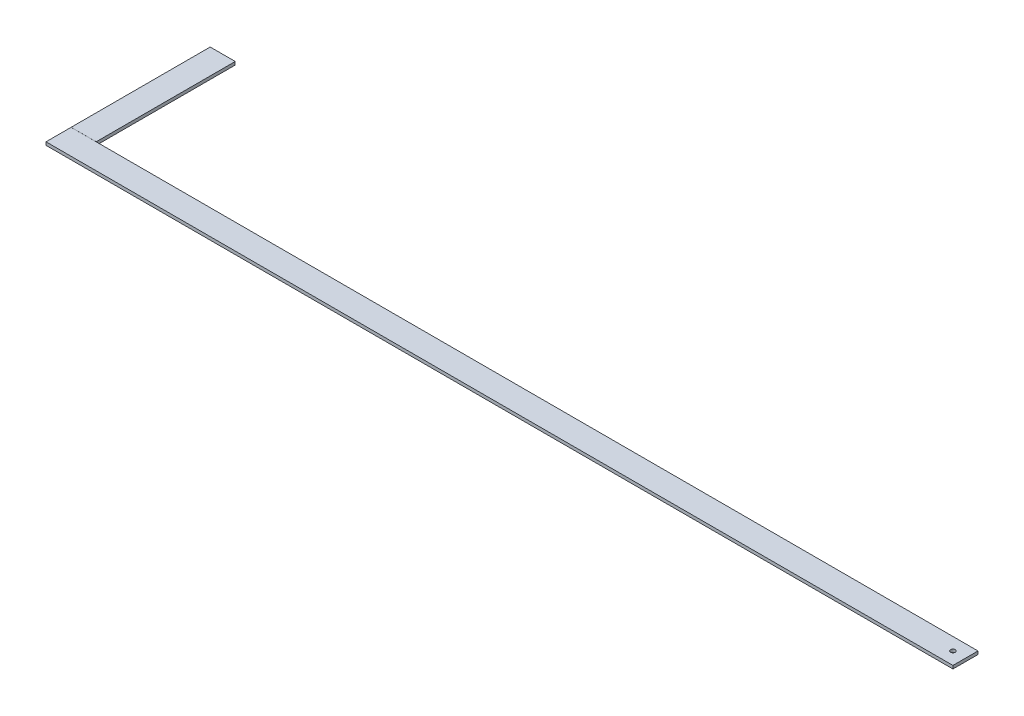
SolidWorks part; units mm, degrees
ref_plane "Alzado" through (0, 0, 0) normal (0, 0, 1) x (1, 0, 0)
ref_plane "Planta" through (0, 0, 0) normal (0, 1, 0) x (1, 0, 0)
ref_plane "Vista lateral" through (0, 0, 0) normal (1, 0, 0) x (0, 0, -1)
sketch "Croquis2" plane through (0, 0, 0) normal (0, 0, 1) x (1, 0, 0)
  line L1 (-25.4, 67.5) -> (25.4, 67.5)
  line L2 (-25.4, 67.5) -> (-25.4, -67.5)
  line L3 (-25.4, -67.5) -> (25.4, -67.5)
  line L4 (25.4, 67.5) -> (25.4, -67.5)
  line L5 (-25.4, 67.5) -> (25.4, -67.5) construction
  line L6 (-25.4, -67.5) -> (25.4, 67.5) construction
  point P0 (0, 0)
  dimension "D1" = 135
  dimension "D2" = 50.8
extrude "Saliente-Extruir1" add sketch "Croquis2" along normal blind 6.31
sketch "Croquis3" plane through (0, 0, 6.31) normal (0, 0, 1) x (1, 0, 0)
  line L1 (-25.4, -61.19) -> (25.4, -61.19)
  line L2 (-25.4, -61.19) -> (-25.4, -67.5)
  line L3 (-25.4, -67.5) -> (25.4, -67.5)
  line L4 (25.4, -61.19) -> (25.4, -67.5)
  line L5 (-25.4, -61.19) -> (25.4, -67.5) construction
  line L6 (-25.4, -67.5) -> (25.4, -61.19) construction
  point P0 (0, -64.345)
  dimension "D1" = 6.31
  dimension "D2" = 50.8
extrude "Saliente-Extruir2" add sketch "Croquis3" along normal blind 513.44
sketch "Croquis4" plane through (25.4, 0, 0) normal (1, 0, 0) x (0, 0, -1)
  line L1 (-468.95, -67.5) -> (-519.75, -67.5)
  line L2 (-468.95, -67.5) -> (-468.95, -61.19)
  line L3 (-468.95, -61.19) -> (-519.75, -61.19)
  line L4 (-519.75, -67.5) -> (-519.75, -61.19)
  line L5 (-468.95, -67.5) -> (-519.75, -61.19) construction
  line L6 (-468.95, -61.19) -> (-519.75, -67.5) construction
  point P0 (-494.35, -64.345)
  dimension "D1" = 50.8
extrude "Saliente-Extruir3" add sketch "Croquis4" along normal blind 1787.3
sketch "Croquis9" plane through (0, 0, 519.75) normal (0, 0, 1) x (1, 0, 0)
  line L0 (1812.7, -61.19) -> (-25.4, -61.19) construction
  line L1 (1761.9, -61.19) -> (1812.7, -61.19)
  line L2 (1761.9, -61.19) -> (1761.9, -67.5)
  line L3 (1761.9, -67.5) -> (1812.7, -67.5)
  line L4 (1812.7, -61.19) -> (1812.7, -67.5)
  line L5 (1761.9, -61.19) -> (1812.7, -67.5) construction
  line L6 (1761.9, -67.5) -> (1812.7, -61.19) construction
  point P0 (1787.3, -64.345)
  dimension "D1" = 50.8
sketch3d "Croquis3D3"
  line L0 (1787.3, -64.345, 519.75) -> (1787.3, -64.345, 642.06)
  line L1 (1787.3, -64.345, 642.06) -> (1787.3, 66.675, 642.06)
  line L2 (1787.3, 66.675, 642.06) -> (1787.3, 66.675, 1436.06)
  dimension "D1" = 122.31
  dimension "D2" = 131.02
  dimension "D3" = 794
sweep "Barrer2" add profiles "Croquis9" path "Croquis3D3"
sketch "Croquis11" plane through (-25.4, 0, 0) normal (-1, 0, 0) x (0, 0, 1)
  line L0 (0, 67.5) -> (-31.6013, 124.8087)
  line L1 (-31.6013, 124.8087) -> (-26.0757, 127.8557)
  line L2 (-26.0757, 127.8557) -> (6.31, 67.5)
  line L3 (0, 67.5) -> (6.31, 67.5)
  line L4 (0, 67.5) -> (0, -67.5) construction
  dimension "D1" = 6.31
  dimension "D2" = 151.127
  dimension "D3" = 65.4441
extrude "Saliente-Extruir4" add sketch "Croquis11" against normal blind 98
sketch "Croquis12" plane through (0, 69.83, 0) normal (0, 1, 0) x (1, 0, 0)
  line L0 (1787.3, -1436.06) -> (1787.3, -1403.06) construction
  line L1 (1787.3, -642.06) -> (1787.3, -1436.06) construction
  line L2 (1787.3, -1403.06) -> (1787.3, -1183.06) construction
  circle A0 centre (1787.3, -1403.06) radius 5
  circle A1 centre (1787.3, -1183.06) radius 5
  dimension "D3" = 10
  dimension "D4" = 10
  dimension "D1" = 33
  dimension "D2" = 220
extrude "Cortar-Extruir1" cut sketch "Croquis12" against normal blind 10
sketch "Croquis13" plane through (1812.7, 0, 0) normal (1, 0, 0) x (0, 0, -1)
  line L0 (-645.215, 56.7163) -> (-638.905, 56.7163)
  line L1 (-645.215, -67.5) -> (-645.215, 63.52) construction
  line L2 (-638.905, -61.19) -> (-638.905, 69.83) construction
  line L3 (-638.905, 56.7163) -> (-638.905, 69.83)
  line L4 (-638.905, 69.83) -> (-1436.06, 69.83)
  line L5 (-1436.06, 69.83) -> (-1436.06, 63.52)
  line L6 (-1436.06, 63.52) -> (-645.215, 63.52)
  line L7 (-645.215, 63.52) -> (-645.215, 56.7163)
  dimension "D1" = 13.1137
extrude "Cortar-Extruir2" cut sketch "Croquis13" against normal blind 73
sketch "Croquis16" plane through (0, 17.7188, 33.0216) normal (0, 0.4728, 0.8812) x (1, 0, 0)
  line L0 (25.4, 56.495) -> (25.4, 124.9905)
  line L1 (72.6, 124.9905) -> (-25.4, 124.9905) construction
  line L2 (25.4, 124.9905) -> (72.6, 124.9905)
  line L3 (72.6, 124.9905) -> (72.6, 56.495)
  line L4 (72.6, 56.495) -> (25.4, 56.495)
extrude "Cortar-Extruir5" cut sketch "Croquis16" against normal blind 10
sketch "Croquis17" plane through (0, -61.19, 0) normal (0, 1, 0) x (1, 0, 0)
  line L0 (25.4, -468.95) -> (-25.4, -468.95)
  line L1 (-25.4, -519.75) -> (-25.4, -6.31) construction
  line L2 (-25.4, -468.95) -> (-25.4, -468.85)
  line L3 (-25.4, -468.85) -> (25.4, -468.85)
  line L4 (25.4, -468.95) -> (25.4, -6.31) construction
  line L5 (25.4, -468.85) -> (25.4, -468.95)
  dimension "D1" = 0.1
extrude "Cortar-Extruir6" cut sketch "Croquis17" against normal blind 50.8
sketch "Croquis18" plane through (0, -61.19, 0) normal (0, 1, 0) x (1, 0, 0)
  line L0 (1761.9, -519.75) -> (1812.7, -519.75)
  line L1 (1812.7, -468.95) -> (1812.7, -638.905) construction
  line L2 (1812.7, -519.75) -> (1812.7, -519.85)
  line L3 (1812.7, -519.85) -> (1761.9, -519.85)
  line L4 (1761.9, -519.75) -> (1761.9, -638.905) construction
  line L5 (1761.9, -519.85) -> (1761.9, -519.75)
  dimension "D1" = 0.1
extrude "Cortar-Extruir7" cut sketch "Croquis18" against normal blind 50.8
sketch "Croquis19" plane through (0, -67.5, 0) normal (0, -1, 0) x (-1, 0, 0)
  line L0 (-1092.1469, -494.5495) -> (-1096.9077, -494.35) construction
  line L1 (-1096.9077, -494.35) -> (-1114.2705, -494.35) construction
  line L2 (-1135.4077, -494.35) -> (-1058.4077, -494.35) construction
  circle A0 centre (-1096.9077, -494.35) radius 4.765 construction
  circle A1 centre (-1096.9077, -494.35) radius 5
  dimension "D1" = 10
sketch "Croquis20" plane through (0, 0, 638.905) normal (0, 0, -1) x (-1, 0, 0)
  line L0 (-1787.3, 56.7163) -> (-1787.3, 22.7163) construction
  line L1 (-1761.9, 56.7163) -> (-1812.7, 56.7163) construction
  line L2 (-1787.3, -64.345) -> (-1787.3, 66.675) construction
  circle A0 centre (-1787.3, 22.7163) radius 5
  dimension "D2" = 10
  dimension "D1" = 34
extrude "Cortar-Extruir9" cut sketch "Croquis20" against normal blind 33
sketch "Croquis21" plane through (0, -67.5, 0) normal (0, -1, 0) x (-1, 0, 0)
  circle A0 centre (-900.0979, -457.445) radius 5
  circle A1 centre (-874.6979, -432.045) radius 5
sketch "Croquis24" plane through (0, -67.5, 0) normal (0, -1, 0) x (-1, 0, 0)
  circle A0 centre (-1800.0979, -507.05) radius 4.7625
  circle A1 centre (-1774.6979, -481.65) radius 4.7625
sketch "Croquis25" plane through (0, -67.5, 0) normal (0, -1, 0) x (-1, 0, 0)
  line L0 (-1782.7036, -493.1032) -> (-1787.3, -494.35) construction
  line L1 (-1787.3, -494.35) -> (-1787.3, -489.5875) construction
  circle A0 centre (-1787.3, -494.35) radius 4.7625 construction
  circle A1 centre (-1787.3, -494.35) radius 4.7625
extrude "Cortar-Extruir13" cut sketch "Croquis25" against normal blind 50
sketch "Croquis29" plane through (0, 56.7163, 0) normal (0, 1, 0) x (1, 0, 0)
  line L0 (1761.9, -645.215) -> (1761.9, -638.905)
  line L1 (1761.9, -638.905) -> (1812.7, -638.905)
  line L2 (1812.7, -638.905) -> (1812.7, -645.215)
  line L3 (1812.7, -645.215) -> (1761.9, -645.215)
extrude "Saliente-Extruir5" add sketch "Croquis29" along normal blind 100
sketch "Croquis31" plane through (1812.7, 0, 0) normal (1, 0, 0) x (0, 0, -1)
  line L0 (-519.85, -61.19) -> (-519.85, -67.5)
  line L1 (-519.85, -67.5) -> (-645.215, -67.5)
  line L2 (-645.215, -67.5) -> (-645.215, 156.7163)
  line L3 (-645.215, 156.7163) -> (-638.905, 156.7163)
  line L4 (-638.905, 156.7163) -> (-638.905, -61.19)
  line L5 (-638.905, -61.19) -> (-519.85, -61.19)
sketch "Croquis32" plane through (-25.4, 0, 0) normal (-1, 0, 0) x (0, 0, 1)
  line L0 (6.31, -61.19) -> (0, -61.19)
  line L1 (0, 67.5) -> (0, -67.5) construction
  line L2 (0, -61.19) -> (0, 67.5)
  line L3 (0, 67.5) -> (-31.6013, 124.8087)
  line L4 (-31.6013, 124.8087) -> (-26.0757, 127.8557)
  line L5 (-26.0757, 127.8557) -> (6.31, 67.5)
  line L6 (6.31, 67.5) -> (6.31, -61.19)
extrude "Cortar-Extruir17" cut sketch "Croquis32" against normal blind 68
sketch "Croquis33" plane through (0, -61.19, 0) normal (0, 1, 0) x (1, 0, 0)
  line L0 (-25.4, 0) -> (-25.4, -187)
  line L1 (-25.4, -468.85) -> (-25.4, 0) construction
  line L2 (-25.4, -187) -> (25.4, -187)
  line L3 (25.4, -468.85) -> (25.4, 0) construction
  line L4 (25.4, -187) -> (25.4, 0)
  line L5 (25.4, 0) -> (-25.4, 0)
  dimension "D1" = 187
extrude "Cortar-Extruir18" cut sketch "Croquis33" against normal blind 74
sketch "Croquis34" plane through (1812.7, 0, 0) normal (1, 0, 0) x (0, 0, -1)
  line L0 (-519.85, -61.19) -> (-519.85, -67.5)
  line L1 (-519.85, -67.5) -> (-645.215, -67.5)
  line L2 (-645.215, -67.5) -> (-645.215, 156.7163)
  line L3 (-645.215, 156.7163) -> (-638.905, 156.7163)
  line L4 (-638.905, 156.7163) -> (-638.905, -61.19)
  line L5 (-638.905, -61.19) -> (-519.85, -61.19)
extrude "Cortar-Extruir19" cut sketch "Croquis34" against normal blind 121
